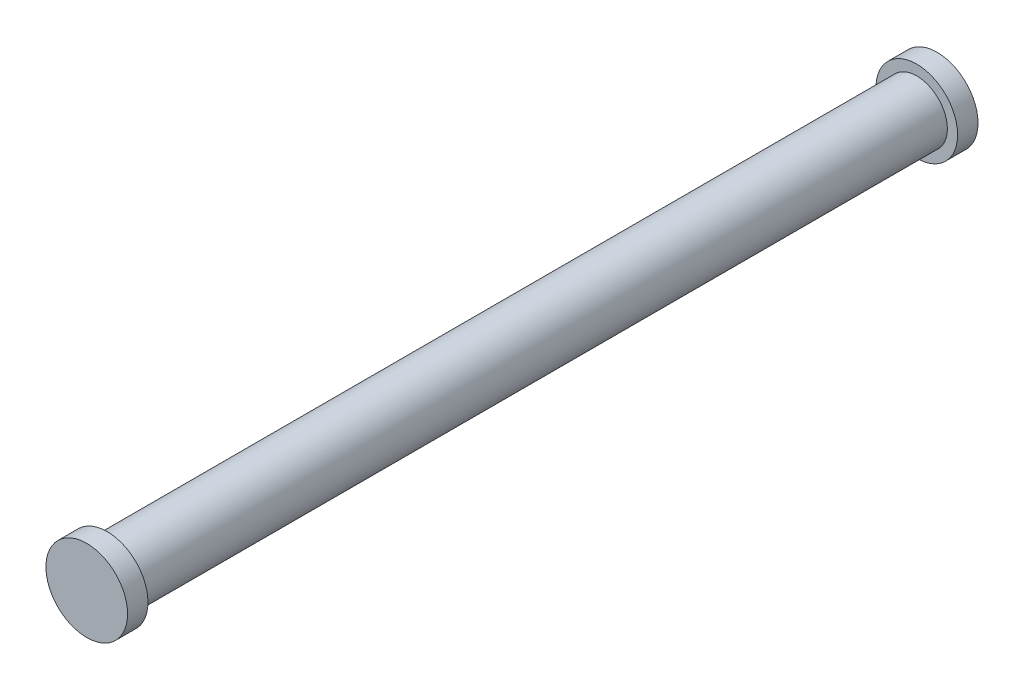
SolidWorks part; units mm, degrees
ref_plane "Front Plane" through (0, 0, 0) normal (0, 0, 1) x (1, 0, 0)
ref_plane "Top Plane" through (0, 0, 0) normal (0, 1, 0) x (1, 0, 0)
ref_plane "Right Plane" through (0, 0, 0) normal (1, 0, 0) x (0, 0, -1)
sketch "Sketch2" plane through (0, 0, 0) normal (0, 0, 1) x (1, 0, 0)
  circle A0 centre (0, 0) radius 15
  dimension "D1" = 30
extrude "Boss-Extrude1" add sketch "Sketch2" along normal mid plane 396.67
sketch "Sketch3" plane through (0, 0, 198.335) normal (0, 0, 1) x (1, 0, 0)
  circle A2 centre (0, 0) radius 20
  dimension "D1" = 40
extrude "Boss-Extrude2" add sketch "Sketch3" along normal blind 10
mirror "Mirror1" about plane through (0, 0, 0) normal (0, 0, 1) of "Boss-Extrude2"
